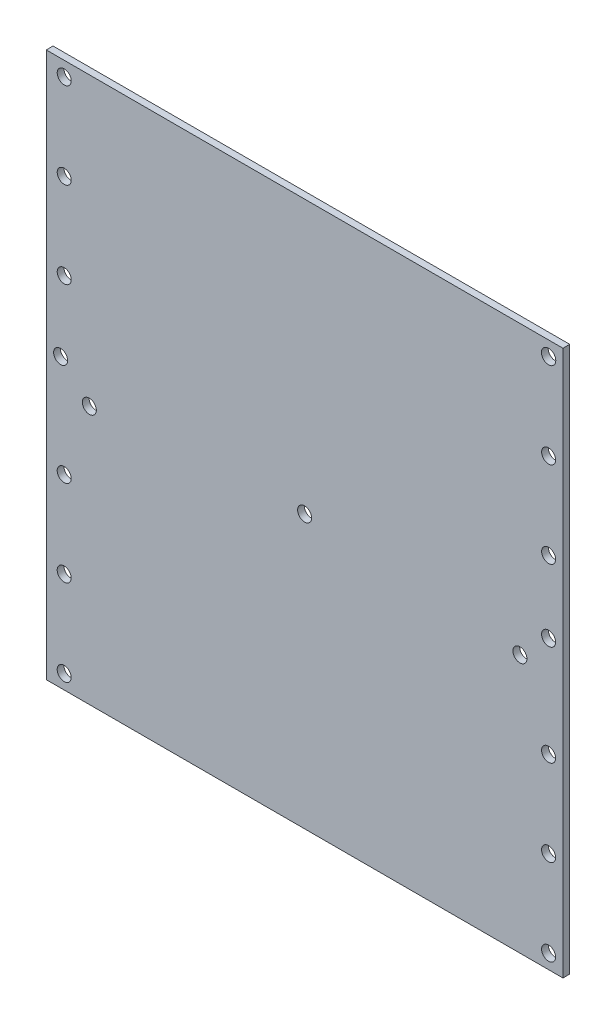
SolidWorks part; units mm, degrees
ref_plane "Front" through (0, 0, 0) normal (0, 0, 1) x (1, 0, 0)
ref_plane "Top" through (0, 0, 0) normal (0, 1, 0) x (1, 0, 0)
ref_plane "Right" through (0, 0, 0) normal (1, 0, 0) x (0, 0, -1)
sketch "Sketch1" plane through (0, 0, 0) normal (0, 0, 1) x (1, 0, 0)
  line L0 (-57.15, 60.325) -> (57.15, 60.325)
  line L1 (57.15, 60.325) -> (57.15, -60.325)
  line L2 (-57.15, 60.325) -> (-57.15, -60.325)
  line L5 (-57.15, -60.325) -> (57.15, -60.325)
extrude "Extrude1" add sketch "Sketch1" along normal blind 1.5
sketch "Sketch2" plane through (0, 0, 1.5) normal (0, 0, 1) x (1, 0, 0)
  circle A0 centre (-53.975, 3.175) radius 1.55
  circle A1 centre (-47.625, -3.175) radius 1.55
  circle A2 centre (53.975, 3.175) radius 1.55
  circle A3 centre (47.625, -3.175) radius 1.55
  circle A4 centre (0, 0) radius 1.55
  circle A5 centre (-53.1812, 57.15) radius 1.55
  circle A6 centre (-53.1812, -19.05) radius 1.55
  circle A7 centre (-53.1812, 38.1) radius 1.55
  circle A8 centre (-53.1812, 19.05) radius 1.55
  circle A9 centre (-53.1812, -38.1) radius 1.55
  circle A10 centre (-53.1812, -57.15) radius 1.55
  circle A11 centre (53.975, 57.15) radius 1.5875
  circle A12 centre (53.975, 38.1) radius 1.55
  circle A13 centre (53.975, 19.05) radius 1.55
  circle A14 centre (53.975, -19.05) radius 1.55
  circle A15 centre (53.975, -38.1) radius 1.55
  circle A16 centre (53.975, -57.15) radius 1.55
extrude "Cut-Extrude1" cut sketch "Sketch2" against normal through all
